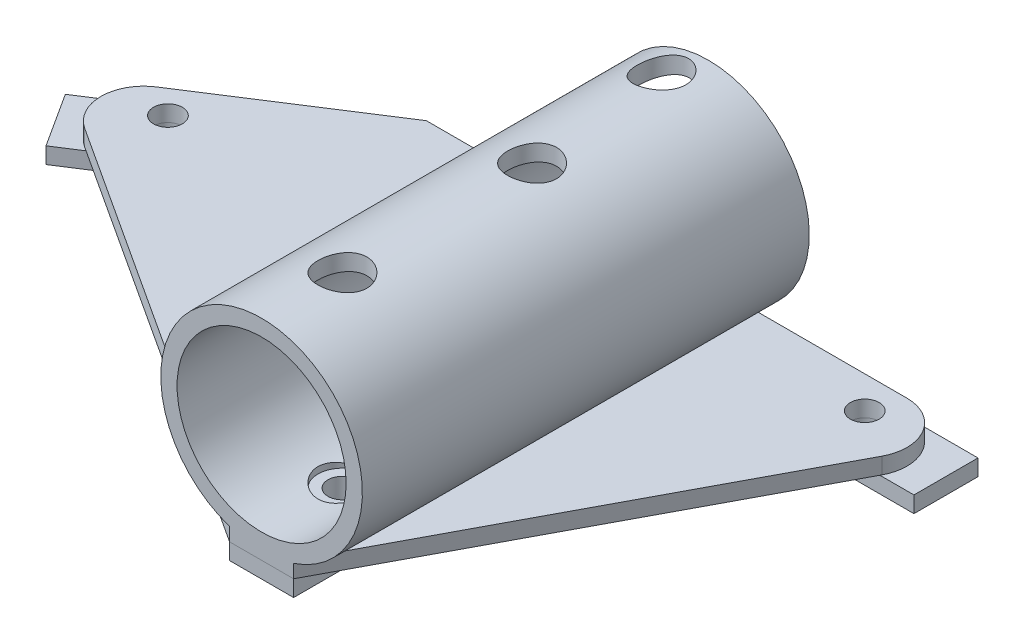
SolidWorks part; units mm, degrees
ref_plane "Front Plane" through (0, 0, 0) normal (0, 0, 1) x (1, 0, 0)
ref_plane "Top Plane" through (0, 0, 0) normal (0, 1, 0) x (1, 0, 0)
ref_plane "Right Plane" through (0, 0, 0) normal (1, 0, 0) x (0, 0, -1)
sketch "Sketch1" plane through (0, 0, 0) normal (0, 1, 0) x (1, 0, 0)
  line L1 (-94.6799, 33.0933) -> (34.6061, 33.0933)
  line L3 (-90.0571, 18.0819) -> (-36.0694, 18.0819)
  line L4 (34.6061, 33.0933) -> (34.6061, 18.0819)
  line L5 (-94.6799, 33.0933) -> (-146.1424, -0.0543)
  line L6 (-90.0571, 18.0819) -> (-137.9531, -12.7684)
  line L8 (-146.1424, -0.0543) -> (-137.9531, -12.7684)
  line L9 (-21.058, 18.0819) -> (34.6061, 18.0819)
  line L11 (-36.0694, 18.0819) -> (-36.0694, -71.6309)
  line L12 (-36.0694, -71.6309) -> (-21.058, -71.6309)
  line L13 (-21.058, 18.0819) -> (-21.058, -71.6309)
  point P10 (-28.5637, -71.6309)
  dimension "D1" = 15.0114
  dimension "D2" = 129.286
  dimension "D3" = 124.6632
  dimension "D4" = 61.214
  dimension "D5" = 15.0114
  dimension "D6" = 89.7128
  dimension "D7" = 61.4934
extrude "Boss-Extrude1" add sketch "Sketch1" along normal blind 3.81
sketch "Sketch4" plane through (0, 3.81, 0) normal (0, 1, 0) x (1, 0, 0)
  line L0 (-146.1424, -0.0543) -> (-94.6799, 33.0933)
  line L1 (-94.6799, 33.0933) -> (34.6061, 33.0933)
  line L3 (-146.1424, -0.0543) -> (-36.0694, -71.6309)
  line L6 (34.6061, 33.0933) -> (-21.058, -71.6309)
  line L7 (-21.058, -71.6309) -> (-36.0694, -71.6309)
extrude "Boss-Extrude2" add sketch "Sketch4" along normal blind 3.81 separate body
sketch "Sketch9" plane through (0, 7.62, 0) normal (0, 1, 0) x (1, 0, 0)
  line L1 (-36.0694, -71.6309) -> (-21.058, -71.6309)
  line L2 (-36.0694, -71.6309) -> (-36.0694, 18.0819)
  line L4 (-21.058, -71.6309) -> (-21.058, 18.0819)
  line L5 (-36.0694, 33.0933) -> (-21.058, 33.0933)
  line L7 (34.6061, 33.0933) -> (-94.6799, 33.0933) construction
  line L8 (-21.058, 33.0933) -> (-21.058, 18.0819)
  arc A0 (-36.0694, 33.0933) -> (-36.0694, 18.0819) centre (-36.0694, 25.5876) ccw
extrude "Boss-Extrude3" add sketch "Sketch9" along normal blind 3.81
sketch "Sketch13" plane through (0, 0, 71.6309) normal (0, 0, 1) x (1, 0, 0)
  line L0 (-36.0694, 11.43) -> (-21.058, 11.43) construction
  line L1 (-36.0694, 11.0018) -> (-36.0694, 6.9392)
  line L2 (-36.0694, 11.43) -> (-36.0694, 7.62) construction
  line L3 (-36.0694, 7.62) -> (-36.0694, 3.81) construction
  line L4 (-21.058, 11.0018) -> (-21.058, 6.9392)
  line L5 (-21.058, 7.62) -> (-21.058, 3.81) construction
  arc A0 (-21.058, 11.0018) -> (-36.0694, 11.0018) centre (-28.5637, 29.337) ccw
  arc A1 (-21.058, 6.9392) -> (-36.0694, 6.9392) centre (-28.5637, 29.337) ccw
  point P4 (-28.5637, 11.43)
  dimension "D3" = 39.624
extrude "Boss-Extrude4" add sketch "Sketch13" against normal through all
sketch "Sketch2" plane through (0, 3.81, 0) normal (0, 1, 0) x (1, 0, 0)
  line L0 (-137.9531, -12.7684) -> (-90.0571, 18.0819) construction
  line L1 (-146.1424, -0.0543) -> (-137.9531, -12.7684) construction
  line L2 (-90.0571, 18.0819) -> (-36.0694, 18.0819) construction
  line L3 (-36.0694, 18.0819) -> (-21.058, 18.0819) construction
  line L4 (-21.058, 18.0819) -> (34.6061, 18.0819) construction
  line L6 (-21.058, -71.6309) -> (-21.058, 18.0819) construction
  line L7 (-94.6799, 33.0933) -> (-90.0571, 18.0819) construction
  circle A0 centre (-125.9953, 3.8466) radius 3.3782
  circle A1 centre (-75.0965, 25.5749) radius 3.3782
  circle A2 centre (-32.0435, 25.5749) radius 3.3782
  circle A3 centre (15.5815, 25.5749) radius 3.3782
  circle A4 centre (-28.678, -8.1309) radius 3.3782
  circle A5 centre (-28.678, -52.5809) radius 3.3782
  point P28 (-28.5637, 18.0819)
  dimension "D1" = 6.7564
  dimension "D4" = 6.7564
  dimension "D7" = 6.7564
  dimension "D12" = 6.7564
  dimension "D15" = 6.7564
  dimension "D3" = 19.05
  dimension "D6" = 7.493
  dimension "D8" = 43.053
  dimension "D9" = 7.493
  dimension "D10" = 47.625
  dimension "D11" = 7.493
  dimension "D5" = 55.3426
  dimension "D14" = 26.2128
  dimension "D13" = 7.62
  dimension "D16" = 44.45
extrude "Cut-Extrude1" cut sketch "Sketch2" along a picked direction on the side of the normal mid plane 15.24
sketch "Sketch18" plane through (0, 11.43, 0) normal (0, 1, 0) x (1, 0, 0)
  circle A0 centre (-28.678, -52.5809) radius 5.715
  circle A1 centre (-28.678, -8.1309) radius 5.715
  circle A2 centre (-32.0435, 25.5749) radius 5.715
  dimension "D1" = 11.43
  dimension "D2" = 11.43
  dimension "D3" = 11.43
extrude "Cut-Extrude3" cut sketch "Sketch18" against normal blind 2.54 and the other way blind 45.974
sketch "Sketch20" plane through (0, 0, 71.6309) normal (0, 0, 1) x (1, 0, 0)
  line L0 (-37.0404, 11.43) -> (-20.087, 11.43)
  line L1 (-36.0694, 11.43) -> (-21.058, 11.43) construction
  arc A0 (-37.0404, 11.43) -> (-20.087, 11.43) centre (-28.5637, 29.337) ccw
  point P10 (-37.0404, 11.43)
extrude "Cut-Extrude5" cut sketch "Sketch20" against normal through all
sketch "Sketch21" plane through (0, 0, 71.6309) normal (0, 0, 1) x (1, 0, 0)
  line L0 (-43.5751, 7.62) -> (-37.8573, 7.62)
  line L1 (-146.1424, 7.62) -> (-37.8573, 7.62) construction
  line L2 (-43.5751, 9.3591) -> (-43.5751, 7.62)
  line L3 (-43.5751, 11.0981) -> (-43.5751, 7.62) construction
  line L4 (-43.5751, 9.3591) -> (-43.5751, 11.0981)
  arc A0 (-43.5751, 11.0981) -> (-37.8573, 7.62) centre (-28.5637, 29.337) ccw
  arc A1 (-21.058, 6.9392) -> (-36.0694, 6.9392) centre (-28.5637, 29.337) ccw construction
  dimension "D1" = 0
  dimension "D2" = 47.244
extrude "Cut-Extrude7" cut sketch "Sketch21" against normal through all
fillet "Fillet1" radius 10 1 edges at (34.6061, 5.715, -33.0933)
fillet "Fillet2" radius 10 1 edges at (-146.1424, 5.715, 0.0543)
equation "\"width\"= 0.591"
equation "\"D1@Sketch1\"=\"width\""
equation "\"D5@Sketch1\"=\"width\""
equation "\"hole diameter\"= 0.266"
equation "\"D1@Sketch2\"=\"hole diameter\""
equation "\"D4@Sketch2\"=\"hole diameter\""
equation "\"D7@Sketch2\"=\"hole diameter\""
equation "\"D12@Sketch2\"=\"hole diameter\""
equation "\"D15@Sketch2\"=\"hole diameter\""
equation "\"ac diameter\"= 1.56"
equation "\"height\"= 0.15"
equation "\"D1@Boss-Extrude3\"= \"height\""
equation "\"D1@Boss-Extrude1\"= \"height\""
equation "\"D1@Boss-Extrude2\"= \"height\""
equation "\"D1@Cut-Extrude1\"= \"height\""
equation "\"D2@Cut-Extrude1\"= \"height\" * 2"
equation "\"outer diamter\"= 0.45"
equation "\"D1@Sketch18\"= \"outer diamter\""
equation "\"D2@Sketch18\"= \"outer diamter\""
equation "\"D3@Sketch18\"= \"outer diamter\""
equation "\"D1@Cut-Extrude3\"=0.1"
equation "\"D2@Sketch13\"=\"height\""
equation "\"D2@Sketch21\"=\"height\"*2+1.56"
